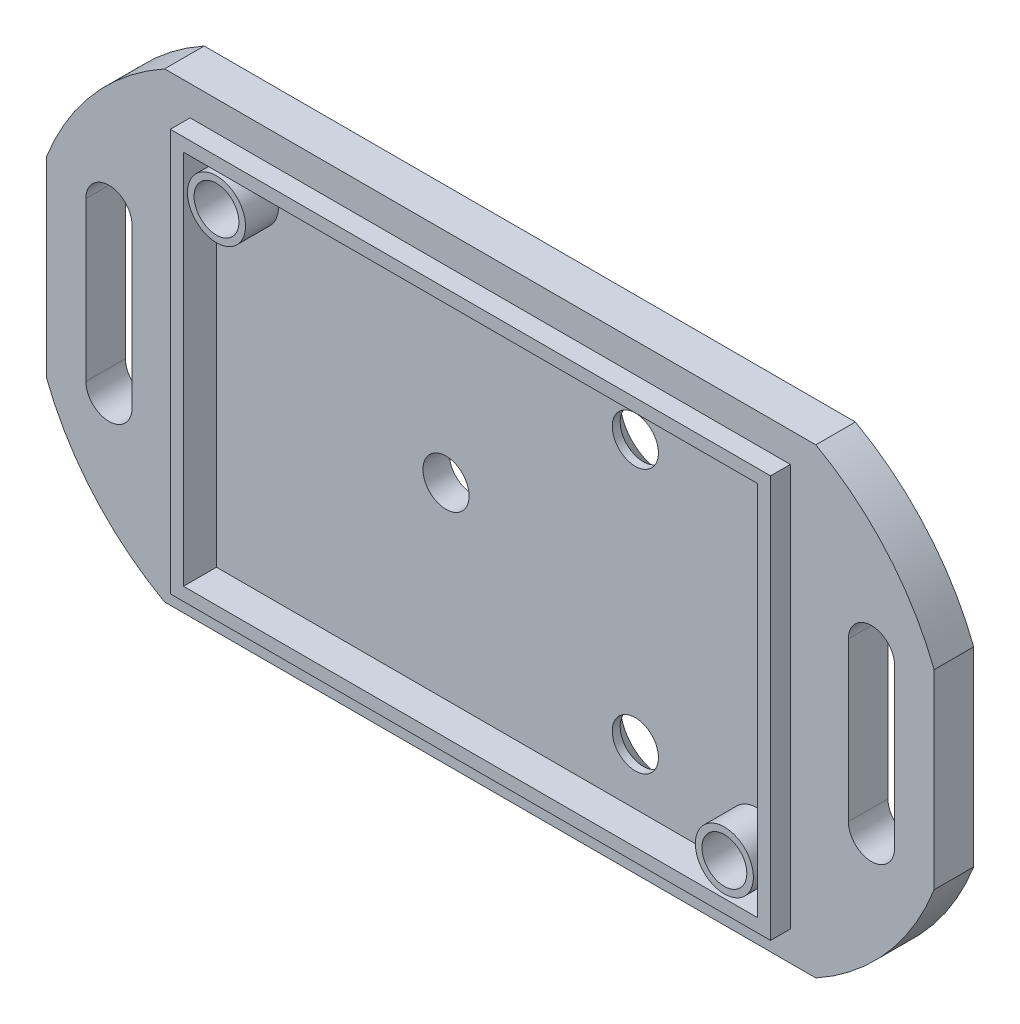
SolidWorks part; units mm, degrees
ref_plane "Plan de face" through (0, 0, 0) normal (0, 0, 1) x (1, 0, 0)
ref_plane "Plan de dessus" through (0, 0, 0) normal (0, 1, 0) x (1, 0, 0)
ref_plane "Plan de droite" through (0, 0, 0) normal (1, 0, 0) x (0, 0, -1)
sketch "Esquisse1" plane through (0, 0, 0) normal (0, 0, 1) x (1, 0, 0)
  line L1 (-24.6825, 17.5) -> (24.6825, 17.5)
  line L2 (-33.65, 7.2234) -> (-33.65, -7.2234)
  line L3 (-24.6825, -17.5) -> (24.6825, -17.5)
  line L4 (33.65, 7.2234) -> (33.65, -7.2234)
  arc A0 (-24.6825, 17.5) -> (-33.65, 7.2234) centre (-15, 0) ccw
  arc A1 (24.6825, -17.5) -> (33.65, -7.2234) centre (15, 0) ccw
  arc A2 (-33.65, -7.2234) -> (-24.6825, -17.5) centre (-15, 0) ccw
  arc A3 (33.65, 7.2234) -> (24.6825, 17.5) centre (15, 0) ccw
  dimension "D1" = 17.5
  dimension "D3" = 33.65
extrude "Boss.-Extru.1" add sketch "Esquisse1" along normal blind 3
sketch "Esquisse2" plane through (0, 0, 3) normal (0, 0, 1) x (1, 0, 0)
  line L1 (-22.75, 15.25) -> (22.75, 15.25)
  line L2 (-22.75, 15.25) -> (-22.75, -15.25)
  line L3 (-22.75, -15.25) -> (22.75, -15.25)
  line L4 (22.75, 15.25) -> (22.75, -15.25)
  dimension "D1" = 15.25
  dimension "D2" = 30.5
  dimension "D3" = 22.75
  dimension "D4" = 45.5
extrude "Boss.-Extru.2" add sketch "Esquisse2" along normal blind 1.5
sketch "Esquisse3" plane through (0, 0, 4.5) normal (0, 0, 1) x (1, 0, 0)
  line L0 (-21.75, 14.25) -> (21.75, 14.25)
  line L5 (21.75, 14.25) -> (21.75, -14.25)
  line L6 (-21.75, -14.25) -> (21.75, -14.25)
  line L7 (-21.75, 14.25) -> (-21.75, -14.25)
extrude "Enlèv. mat.-Extru.2" cut sketch "Esquisse3" against normal blind 2.5
hole_wizard "Fraisage pour vis à tête fraisée M31" positions "Esquisse5" profile "Esquisse4" countersink size "M3" standard "Iso" end condition through all
sketch "Esquisse5" plane through (0, 0, 0) normal (0, 0, -1) x (-1, 0, 0)
  point P0 (-19.25, -11.75)
  point P2 (19.25, 11.75)
  dimension "D1" = 19.25
  dimension "D2" = 19.25
  dimension "D3" = 11.75
  dimension "D4" = 11.75
sketch "Esquisse4" plane through (19.25, -11.75, 0) normal (1, 0, 0) x (0, 1, 0)
  line L0 (0, 0) -> (0, 4.5)
  line L1 (0, 4.5) -> (1.7, 4.5)
  line L2 (1.7, 4.5) -> (1.7, 1.45)
  line L3 (1.7, 1.45) -> (3.15, 0)
  line L5 (3.15, 0) -> (0, 0)
  line L6 (-1.7, 1.45) -> (-3.15, 0) construction
  line L11 (0, -6.35) -> (0, 107.95) construction
  dimension "Diamètre du perçage jusqu'au prochain" = 3.4
  dimension "Profondeur du perçage jusqu'au prochain" = 4.5
  dimension "Diamètre du fraisage entrant" = 6.3
  dimension "Angle du fraisage entrant" = 90
sketch "Esquisse6" plane through (0, 0, 2) normal (0, 0, 1) x (1, 0, 0)
  circle A0 centre (-19.25, 11.75) radius 1.7
  circle A1 centre (19.25, -11.75) radius 1.7
  circle A2 centre (-19.25, 11.75) radius 2.2
  circle A3 centre (19.25, -11.75) radius 2.2
  dimension "D1" = 0.5
  dimension "D2" = 0.5
extrude "Boss.-Extru.3" add sketch "Esquisse6" along normal blind 2.5
sketch "Esquisse7" plane through (0, 0, 0) normal (0, 0, -1) x (-1, 0, 0)
  line L0 (-27.15, 6) -> (-27.15, -6)
  line L1 (-30.65, 6) -> (-30.65, -6)
  line L2 (27.15, 6) -> (27.15, -6)
  line L3 (30.65, 6) -> (30.65, -6)
  arc A0 (-27.15, 6) -> (-30.65, 6) centre (-28.9, 6) ccw
  arc A1 (-30.65, -6) -> (-27.15, -6) centre (-28.9, -6) ccw
  arc A2 (27.15, -6) -> (30.65, -6) centre (28.9, -6) ccw
  arc A3 (30.65, 6) -> (27.15, 6) centre (28.9, 6) ccw
  dimension "D1" = 6
  dimension "D2" = 28.9
  dimension "D3" = 12
  dimension "D4" = 28.9
extrude "Enlèv. mat.-Extru.3" cut sketch "Esquisse7" against normal through all
hole_wizard "Fraisage pour vis à tête fraisée M32" positions "Esquisse9" profile "Esquisse8" countersink size "M3" standard "Iso" end condition through all
sketch "Esquisse9" plane through (0, 0, 0) normal (0, 0, -1) x (-1, 0, 0)
  point P0 (-10, -10)
  point P2 (-10, 10)
  dimension "D1" = 10
  dimension "D2" = 10
  dimension "D3" = 10
  dimension "D4" = 10
sketch "Esquisse8" plane through (10, -10, 0) normal (1, 0, 0) x (0, 1, 0)
  line L0 (0, 0) -> (0, 4.5)
  line L1 (0, 4.5) -> (1.75, 4.5)
  line L2 (1.75, 4.5) -> (1.75, 1.4)
  line L3 (1.75, 1.4) -> (3.15, 0)
  line L5 (3.15, 0) -> (0, 0)
  line L6 (-1.75, 1.4) -> (-3.15, 0) construction
  line L11 (0, -6.35) -> (0, 107.95) construction
  dimension "Diamètre du perçage jusqu'au prochain" = 3.5
  dimension "Profondeur du perçage jusqu'au prochain" = 4.5
  dimension "Diamètre du fraisage entrant" = 6.3
  dimension "Angle du fraisage entrant" = 90
sketch "Esquisse11" plane through (0, 0, 2) normal (0, 0, 1) x (1, 0, 0)
  line L0 (24.6825, 17.5) -> (-24.6825, 17.5) construction
  line L1 (33.65, -7.2234) -> (33.65, 7.2234) construction
  circle A0 centre (-4.35, 0) radius 1.75
  dimension "D1" = 17.5
  dimension "D2" = 38
extrude "Enlèv. mat.-Extru.5" cut sketch "Esquisse11" against normal up to next
